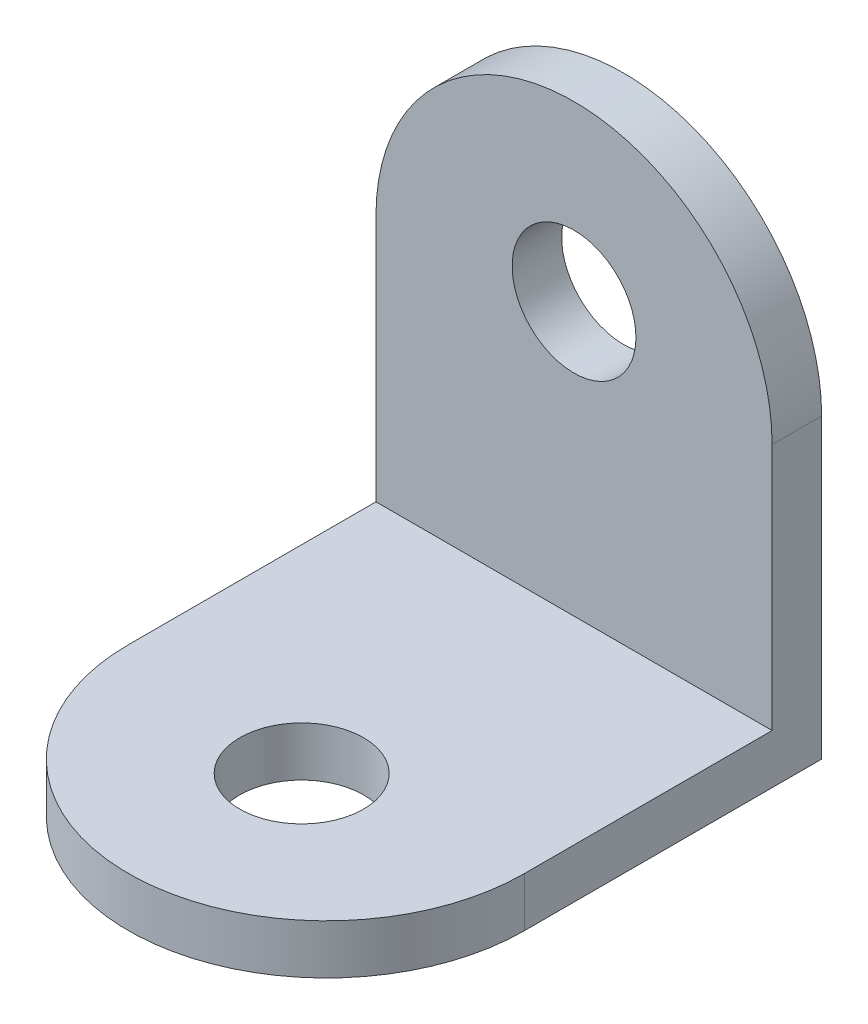
SolidWorks part; units mm, degrees
ref_plane "前视基准面" through (0, 0, 0) normal (0, 0, 1) x (1, 0, 0)
ref_plane "上视基准面" through (0, 0, 0) normal (0, 1, 0) x (1, 0, 0)
ref_plane "右视基准面" through (0, 0, 0) normal (1, 0, 0) x (0, 0, -1)
other "Configuration Table"
sketch "草图1" plane through (0, 0, 0) normal (0, 0, 1) x (1, 0, 0)
  line L0 (-8, 0) -> (-8, -12)
  line L1 (-8, -12) -> (8, -12)
  line L2 (8, -12) -> (8, 0)
  arc A0 (8, 0) -> (-8, 0) centre (0, 0) ccw
  circle A1 centre (0, 1) radius 2.5
  point P1 (0, 8)
  point P9 (0, 0)
  point P10 (0, 0)
  point P11 (-8, 0)
  point P12 (0, 0)
  point P13 (7.4582, -2.9986)
  dimension "D1" = 16
  dimension "D3" = 5
  dimension "D4" = 7
  dimension "D2" = 20
extrude "凸台-拉伸1" add sketch "草图1" along normal blind 2
sketch "草图3" plane through (0, -12, 0) normal (0, -1, 0) x (1, 0, 0)
  line L0 (-8, 12) -> (-8, 0)
  line L1 (-8, 0) -> (8, 0) construction
  line L2 (-8, 0) -> (8, 0)
  line L3 (8, 0) -> (8, 12)
  arc A0 (8, 12) -> (-8, 12) centre (0, 12) ccw
  circle A2 centre (0, 13) radius 2.5
  dimension "D1" = 16
  dimension "D2" = 5
  dimension "D3" = 7
  dimension "D4" = 20
extrude "凸台-拉伸2" add sketch "草图3" against normal blind 2
